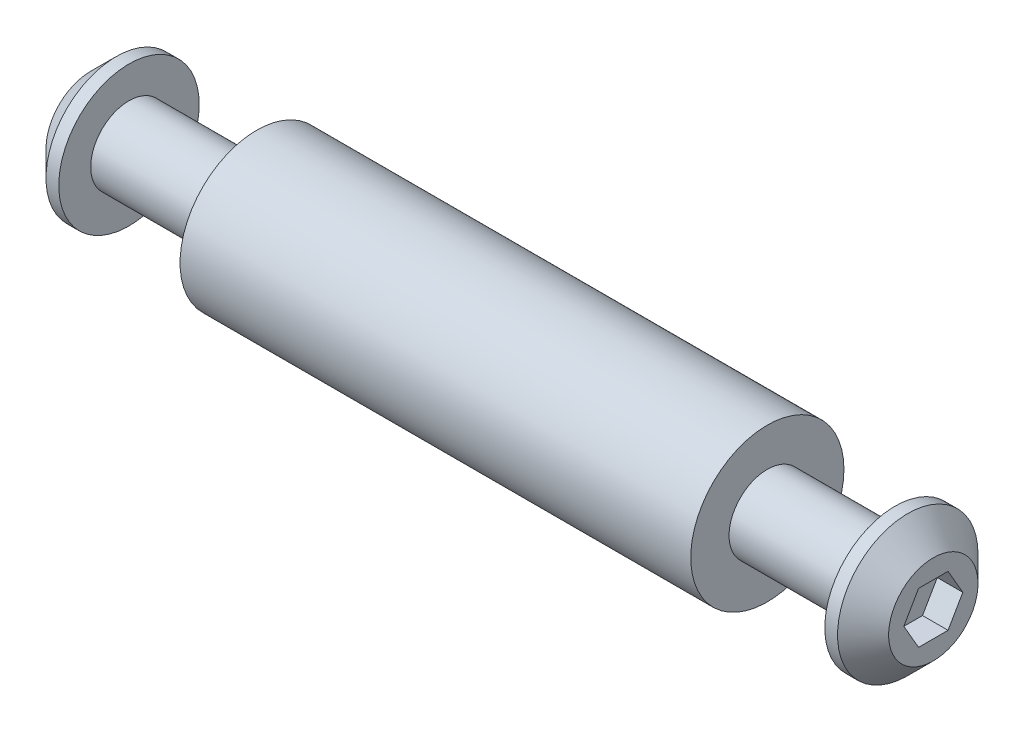
SolidWorks part; units mm, degrees
ref_plane "Front" through (0, 0, 0) normal (0, 0, 1) x (1, 0, 0)
ref_plane "Top" through (0, 0, 0) normal (0, 1, 0) x (1, 0, 0)
ref_plane "Right" through (0, 0, 0) normal (1, 0, 0) x (0, 0, -1)
sketch "Esquisse1" plane through (0, 0, 0) normal (0, 0, 1) x (1, 0, 0)
  line L0 (0, 0) -> (-18.7013, 0) construction
  line L1 (0, 0) -> (0, 7.2882) construction
  line L2 (10, 3) -> (-10, 3)
  line L3 (-10, 3) -> (-10, 1.5)
  line L4 (-10, 1.5) -> (-15, 1.5)
  line L5 (-15, 1.5) -> (-15, 2.75)
  line L6 (-15, 2.75) -> (-15.5, 2.75)
  line L7 (-15.5, 2.75) -> (-16.5, 1.75)
  line L8 (-16.5, 1.75) -> (-16.5, 0)
  line L9 (-16.5, 0) -> (16.5, 0)
  line L10 (10, 3) -> (10, 1.5)
  line L11 (10, 1.5) -> (15, 1.5)
  line L12 (15, 1.5) -> (15, 2.75)
  line L13 (15, 2.75) -> (15.5, 2.75)
  line L14 (15.5, 2.75) -> (16.5, 1.75)
  line L15 (16.5, 1.75) -> (16.5, 0)
  point P7 (-15.25, 2.75)
  point P13 (-15, 2.125)
  point P16 (0, 3)
  point P17 (15, 2.125)
  point P19 (15.25, 2.75)
  dimension "D1" = 3
  dimension "D2" = 6
  dimension "D3" = 20
  dimension "D4" = 5
  dimension "D5" = 1.5
  dimension "D6" = 0.5
  dimension "D7" = 45
  dimension "D8" = 5.5
revolve "Révolution1" add sketch "Esquisse1" angle 360 about L0
sketch "Esquisse2" plane through (16.5, 0, 0) normal (1, 0, 0) x (0, 0, -1)
  line L1 (0.5774, 1) -> (-0.5774, 1)
  line L2 (-0.5774, 1) -> (-1.1547, 0)
  line L3 (-1.1547, 0) -> (-0.5774, -1)
  line L4 (-0.5774, -1) -> (0.5774, -1)
  line L5 (0.5774, -1) -> (1.1547, 0)
  line L6 (1.1547, 0) -> (0.5774, 1)
  circle A0 centre (0, 0) radius 1 construction
  dimension "D1" = 2
extrude "Enlèv. mat.-Extru.1" cut sketch "Esquisse2" against normal blind 1
mirror "Symétrie1" about plane through (0, 0, 0) normal (1, 0, 0) of "Enlèv. mat.-Extru.1"
